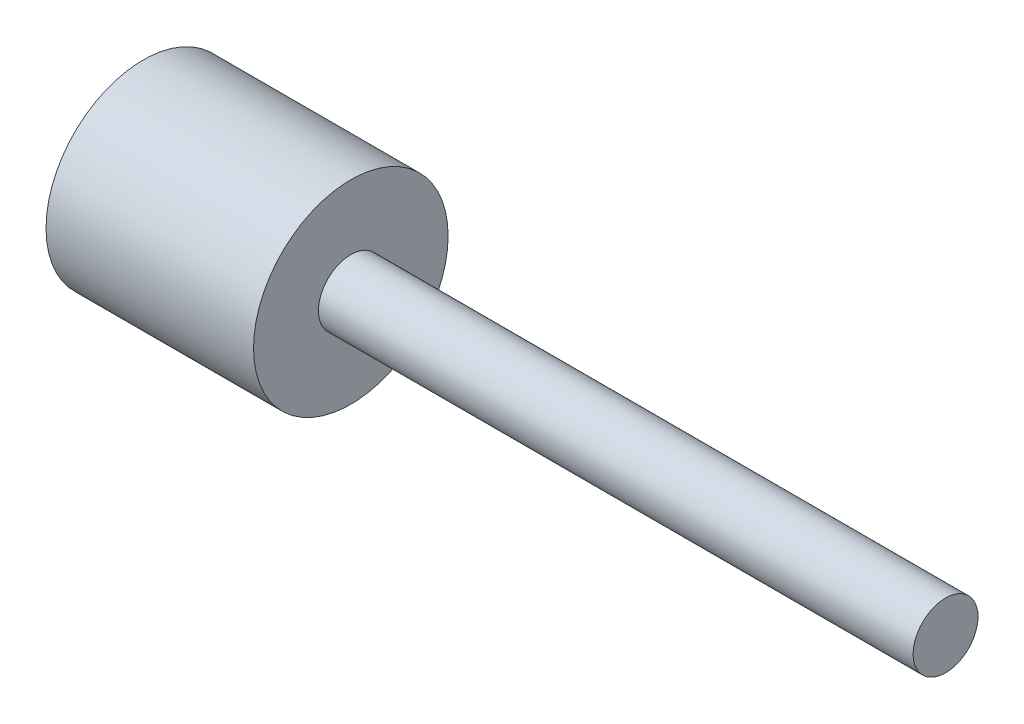
SolidWorks part; units mm, degrees
ref_plane "Front Plane" through (0, 0, 0) normal (0, 0, 1) x (1, 0, 0)
ref_plane "Top Plane" through (0, 0, 0) normal (0, 1, 0) x (1, 0, 0)
ref_plane "Right Plane" through (0, 0, 0) normal (1, 0, 0) x (0, 0, -1)
sketch "Sketch1" plane through (0, 0, 0) normal (1, 0, 0) x (0, 0, -1)
  circle A0 centre (0, 0) radius 7.5
  dimension "D1" = 15
extrude "Boss-Extrude1" add sketch "Sketch1" along normal blind 16
sketch "Sketch2" plane through (16, 0, 0) normal (1, 0, 0) x (0, 0, -1)
  circle A0 centre (0, 0) radius 2.5
  dimension "D1" = 5
extrude "Boss-Extrude2" add sketch "Sketch2" along normal up to vertex (45.85 mm away)
sketch "Sketch3" plane through (0, 0, 0) normal (-1, 0, 0) x (0, 0, 1)
  line L0 (0, 3) -> (0, -2) construction
  line L1 (-2.2361, -2) -> (2.2361, -2) construction
  line L2 (-2.2804, -2.1) -> (2.2804, -2.1)
  arc A0 (2.2361, -2) -> (-2.2361, -2) centre (0, 0) ccw construction
  arc A1 (2.2804, -2.1) -> (-2.2804, -2.1) centre (0, 0) ccw
  dimension "D1" = 6
  dimension "D2" = 5
  dimension "D3" = 0.1
extrude "Cut-Extrude1" cut sketch "Sketch3" against normal blind 12
sketch "Sketch4" plane through (0, -2.1, 0) normal (0, 1, 0) x (1, 0, 0)
  line L0 (0, 0) -> (16, 0) construction
  line L1 (16, -7.5) -> (16, 7.5) construction
  circle A0 centre (5, 0) radius 1.5
  dimension "D1" = 5
  dimension "D2" = 3
extrude "Cut-Extrude2" cut sketch "Sketch4" against normal up to next
